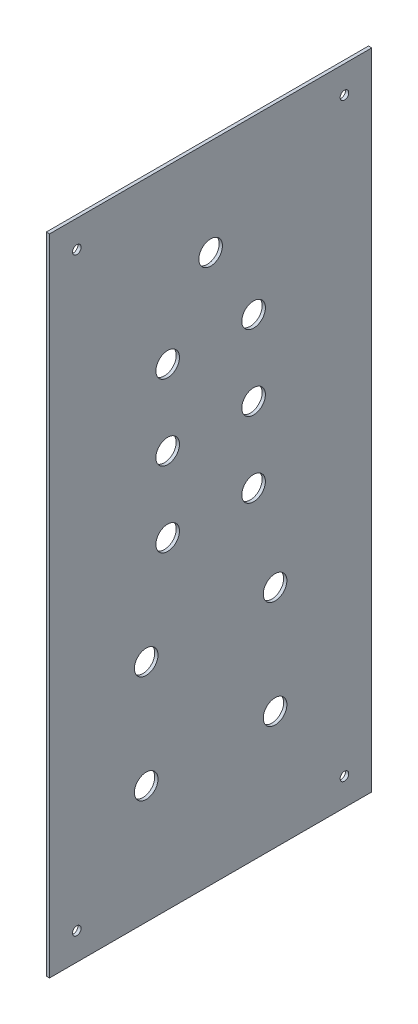
SolidWorks part; units mm, degrees
material "5052-H32"
ref_plane "Front Plane" through (0, 0, 0) normal (1, 0, 0) x (0, 1, 0)
ref_plane "Top Plane" through (0, 0, 0) normal (0, 0, 1) x (0, 1, 0)
ref_plane "Right Plane" through (0, 0, 0) normal (0, 1, 0) x (-1, 0, 0)
sketch "Sketch2" plane through (0, 0, 0) normal (1, 0, 0) x (0, 1, 0)
  line L1 (-150, -75) -> (150, -75)
  line L2 (-150, -75) -> (-150, 75)
  line L3 (-150, 75) -> (150, 75)
  line L4 (150, -75) -> (150, 75)
  line L5 (-150, -75) -> (150, 75) construction
  line L6 (-150, 75) -> (150, -75) construction
  point P0 (0, 0)
extrude "Boss-Extrude1" add sketch "Sketch2" along normal blind 1.52
hole_wizard "Ø4.0 (4) Diameter Hole1" positions "Sketch3" profile "Sketch4" hole size "Ø4.0" standard "ISO" end condition through all
sketch "Sketch3" plane through (1.52, 0, 0) normal (1, 0, 0) x (0, 1, 0)
  line L0 (-150, 75) -> (-150, -75) construction
  line L1 (150, 75) -> (-150, 75) construction
  point P0 (-137.3, 62.3)
  dimension "D1" = 12.7
  dimension "D2" = 12.7
sketch "Sketch4" plane through (1.52, -137.3, 62.3) normal (0, 1, 0) x (0, 0, -1)
  line L0 (0, 0) -> (0, 1.52)
  line L1 (0, 1.52) -> (2, 1.52)
  line L2 (2, 1.52) -> (2, 0)
  line L5 (2, 0) -> (0, 0)
  line L11 (0, -6.35) -> (0, 107.95) construction
  dimension "Thru Hole Dia." = 4
  dimension "Thru Hole Depth" = 1.52
mirror "Mirror1" about plane through (0, 0, 0) normal (0, 1, 0) of "Ø4.0 (4) Diameter Hole1" second plane through (0, 0, 0) second plane normal (0, 0, 1)
hole_wizard "Ø11.0 (11) Diameter Hole4" positions "Sketch5" profile "Sketch6" hole size "Ø11.0" standard "ISO" end condition through all
sketch "Sketch5" plane through (1.52, 0, 0) normal (1, 0, 0) x (0, 1, 0)
  line L0 (-150, 75) -> (-150, -75) construction
  point P0 (-95, 30)
  point P2 (-45, 30)
  point P7 (-150, 0)
  dimension "D1" = 50
  dimension "D2" = 55
  dimension "D3" = 30
sketch "Sketch6" plane through (1.52, -95, 30) normal (0, 1, 0) x (0, 0, -1)
  line L0 (0, 0) -> (0, 1.52)
  line L1 (0, 1.52) -> (5.5, 1.52)
  line L2 (5.5, 1.52) -> (5.5, 0)
  line L5 (5.5, 0) -> (0, 0)
  line L11 (0, -6.35) -> (0, 107.95) construction
  dimension "Thru Hole Dia." = 11
  dimension "Thru Hole Depth" = 1.52
mirror "Mirror2" about plane through (0, 0, 0) normal (0, 0, 1) of "Ø11.0 (11) Diameter Hole4"
hole_wizard "Ø11.0 (11) Diameter Hole2" positions "Sketch8" profile "Sketch9" hole size "Ø11.0" standard "ISO" end condition through all
sketch "Sketch8" plane through (1.52, 0, 0) normal (1, 0, 0) x (0, 1, 0)
  line L0 (150, -75) -> (150, 75) construction
  point P0 (0, 20)
  point P2 (35, 20)
  point P4 (70, 20)
  point P13 (150, 0)
  dimension "D1" = 35
  dimension "D2" = 35
  dimension "D3" = 20
  dimension "D4" = 0
sketch "Sketch9" plane through (1.52, 0, 20) normal (0, 1, 0) x (0, 0, -1)
  line L0 (0, 0) -> (0, 1.52)
  line L1 (0, 1.52) -> (5.5, 1.52)
  line L2 (5.5, 1.52) -> (5.5, 0)
  line L5 (5.5, 0) -> (0, 0)
  line L11 (0, -6.35) -> (0, 107.95) construction
  dimension "Thru Hole Dia." = 11
  dimension "Thru Hole Depth" = 1.52
mirror "Mirror3" about plane through (0, 0, 0) normal (0, 0, 1) of "Ø11.0 (11) Diameter Hole2"
hole_wizard "Ø11.0 (11) Diameter Hole3" positions "Sketch10" profile "Sketch11" hole size "Ø11.0" standard "ISO" end condition through all
sketch "Sketch10" plane through (1.52, 0, 0) normal (1, 0, 0) x (0, 1, 0)
  line L0 (150, -75) -> (150, 75) construction
  circle A0 centre (70, -20) radius 5.5 construction
  point P0 (105, 0)
  point P5 (150, 0)
  dimension "D1" = 35
sketch "Sketch11" plane through (1.52, 105, 0) normal (0, 1, 0) x (0, 0, -1)
  line L0 (0, 0) -> (0, 1.52)
  line L1 (0, 1.52) -> (5.5, 1.52)
  line L2 (5.5, 1.52) -> (5.5, 0)
  line L5 (5.5, 0) -> (0, 0)
  line L11 (0, -6.35) -> (0, 107.95) construction
  dimension "Thru Hole Dia." = 11
  dimension "Thru Hole Depth" = 1.52
